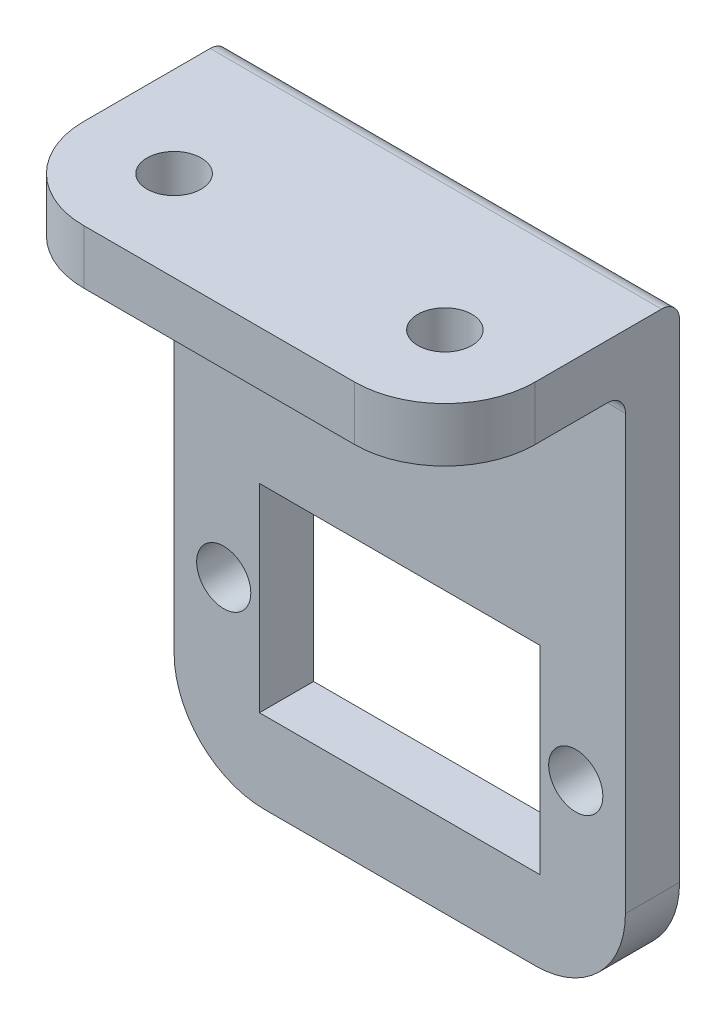
SolidWorks part; units mm, degrees
ref_plane "Front Plane" through (0, 0, 0) normal (0, 0, 1) x (1, 0, 0)
ref_plane "Top Plane" through (0, 0, 0) normal (0, 1, 0) x (1, 0, 0)
ref_plane "Right Plane" through (0, 0, 0) normal (1, 0, 0) x (0, 0, -1)
sketch "Sketch1" plane through (0, 0, 0) normal (0, 0, 1) x (1, 0, 0)
  line L1 (-12.5, -15) -> (12.5, -15)
  line L2 (-12.5, -15) -> (-12.5, 15)
  line L3 (-12.5, 15) -> (12.5, 15)
  line L4 (12.5, -15) -> (12.5, 15)
  line L5 (-12.5, -15) -> (12.5, 15) construction
  line L6 (-12.5, 15) -> (12.5, -15) construction
  circle A0 centre (-9.75, -5) radius 1.5
  circle A1 centre (9.75, -5) radius 1.5
  point P0 (0, 0)
  dimension "D3" = 19.5
  dimension "D4" = 9.75
  dimension "D5" = 3
  dimension "D6" = 3
  dimension "D7" = 20
  dimension "D8" = 20
  dimension "D1" = 30
  dimension "D2" = 25
extrude "Boss-Extrude1" add sketch "Sketch1" along normal blind 3
sketch "Sketch2" plane through (0, 0, 3) normal (0, 0, 1) x (1, 0, 0)
  line L1 (-7.77, 0.5) -> (7.77, 0.5)
  line L2 (-7.77, 0.5) -> (-7.77, -10.5)
  line L3 (-7.77, -10.5) -> (7.77, -10.5)
  line L4 (7.77, 0.5) -> (7.77, -10.5)
  line L8 (-12.5, -15) -> (12.5, -15) construction
  point P4 (0, 0)
  point P5 (0, 0)
  point P12 (0, 0)
  dimension "D1" = 15.54
  dimension "D2" = 11
  dimension "D3" = 4.5
extrude "Cut-Extrude1" cut sketch "Sketch2" against normal through all
fillet "Fillet1" radius 5 2 edges at (12.5, -15, 1.5) (-12.5, -15, 1.5)
sketch "Sketch4" plane through (0, 15, 0) normal (0, 1, 0) x (1, 0, 0)
  line L4 (12.5, 0) -> (-12.5, 0)
  line L5 (-12.5, 0) -> (-12.5, -3)
  line L6 (-12.5, -3) -> (12.5, -3)
  line L7 (12.5, -3) -> (12.5, 0)
  line L8 (12.5, 0) -> (-12.5, 0)
  line L9 (-12.5, 0) -> (-12.5, -3)
  line L10 (-12.5, -3) -> (12.5, -3)
  line L11 (12.5, -3) -> (12.5, 0)
  dimension "D1" = 0
extrude "Boss-Extrude2" add sketch "Sketch4" along normal blind 3
sketch "Sketch5" plane through (0, 0, 3) normal (0, 0, 1) x (1, 0, 0)
  line L0 (12.5, -10) -> (12.5, 18) construction
  line L1 (-12.5, 18) -> (12.5, 18)
  line L2 (-12.5, 18) -> (-12.5, 15)
  line L3 (-12.5, 15) -> (12.5, 15)
  line L4 (12.5, 18) -> (12.5, 15)
  dimension "D1" = 3
extrude "Boss-Extrude3" add sketch "Sketch5" along normal blind 10
fillet "Fillet2" radius 5 1 edges at (12.5, 16.5, 13)
fillet "Fillet3" radius 5 1 edges at (-12.5, 16.5, 13)
sketch "Sketch7" plane through (0, 15, 0) normal (0, -1, 0) x (1, 0, 0)
  circle A0 centre (-7.5, 8) radius 1.5
  circle A1 centre (7.5, 8) radius 1.5
  dimension "D1" = 3
  dimension "D2" = 3
extrude "Cut-Extrude2" cut sketch "Sketch7" against normal through all
fillet "Fillet4" radius 1 1 edges at (0, 15, 3)
fillet "Fillet5" radius 1 1 edges at (0, 18, 0)
